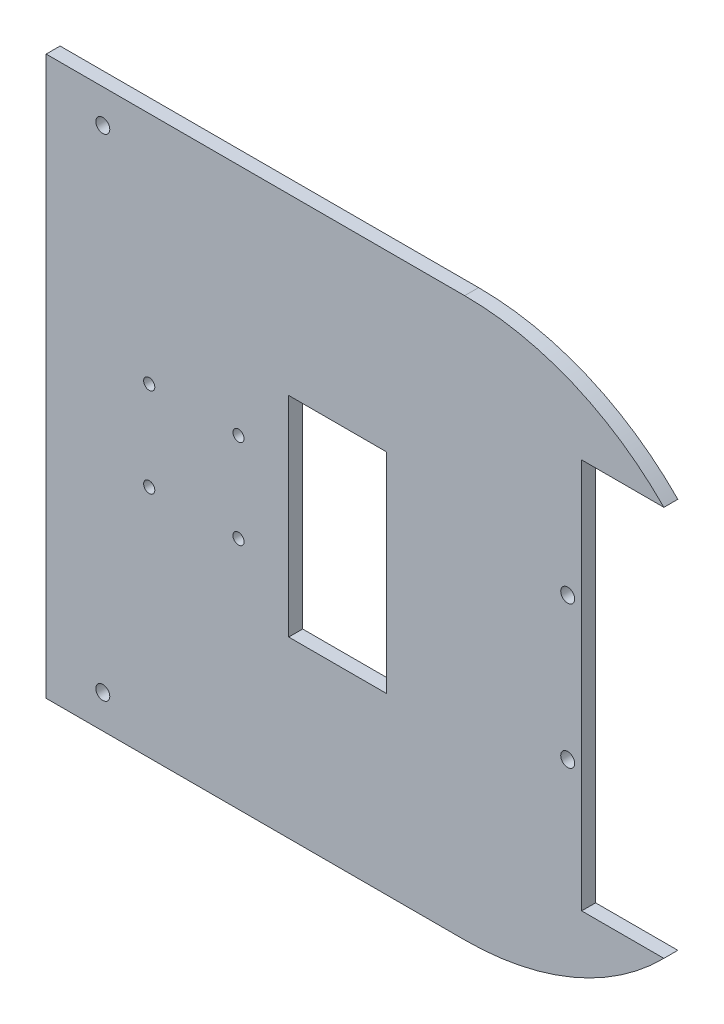
SolidWorks part; units mm, degrees
ref_plane "Front Plane" through (0, 0, 0) normal (0, 0, 1) x (1, 0, 0)
ref_plane "Top Plane" through (0, 0, 0) normal (0, 1, 0) x (1, 0, 0)
ref_plane "Right Plane" through (0, 0, 0) normal (1, 0, 0) x (0, 0, -1)
sketch "Sketch1" plane through (0, 0, 0) normal (0, 0, 1) x (1, 0, 0)
  line L0 (106.477, 150.6351) -> (77, 150.6351)
  line L1 (-264.9373, -19.3649) -> (35.0627, -19.3649)
  line L3 (-264.9373, 180.6351) -> (35.0627, 180.6351)
  line L5 (77, 150.6351) -> (77, 10.6351)
  line L6 (77, 10.6351) -> (106.477, 10.6351)
  line L8 (-306.8745, 10.6351) -> (-336.3515, 10.6351)
  line L9 (-306.8745, 150.6351) -> (-306.8745, 10.6351)
  line L10 (-336.3515, 150.6351) -> (-306.8745, 150.6351)
  arc A0 (35.0627, 180.6351) -> (35.0627, -19.3649) centre (35.0627, 80.6351) cw
  arc A1 (-264.9373, 180.6351) -> (-264.9373, -19.3649) centre (-264.9373, 80.6351) ccw
  point P0 (0, 0)
  point P2 (-364.9373, 80.6351)
  point P7 (135.0627, 80.6351)
  dimension "D2" = 100
  dimension "D3" = 180.6351
  dimension "D4" = 100
  dimension "D5" = 157.3021
  dimension "D6" = 373.7395
  dimension "D7" = 100
  dimension "D8" = 100
  dimension "D16" = 71.4143
  dimension "D15" = 30
  dimension "D1" = 200
  dimension "D9" = 30
  dimension "D10" = 30
  dimension "D11" = 77
  dimension "D12" = 270
  dimension "D13" = 383.8745
  dimension "D14" = 30
extrude "Boss-Extrude1" add sketch "Sketch1" against normal blind 5
sketch "Sketch2" plane through (0, 0, -5) normal (0, 0, -1) x (-1, 0, 0)
  line L5 (264.9373, -19.3649) -> (-35.0627, -19.3649) construction
  line L7 (114.9373, 180.6351) -> (114.9373, -19.3649) construction
  line L8 (264.9373, 180.6351) -> (-35.0627, 180.6351) construction
  line L15 (306.8745, 150.6351) -> (306.8745, 10.6351) construction
  line L16 (201.8745, 118.1351) -> (236.8745, 118.1351)
  line L17 (201.8745, 118.1351) -> (201.8745, 43.1351)
  line L18 (201.8745, 43.1351) -> (236.8745, 43.1351)
  line L19 (236.8745, 118.1351) -> (236.8745, 43.1351)
  line L20 (264.9373, -19.3649) -> (-35.0627, -19.3649) construction
  line L21 (28, 118.1351) -> (-7, 118.1351)
  line L22 (28, 118.1351) -> (28, 43.1351)
  line L23 (28, 43.1351) -> (-7, 43.1351)
  line L24 (-7, 118.1351) -> (-7, 43.1351)
  line L26 (306.8745, 80.6351) -> (-77, 80.6351) construction
  line L27 (-77, 150.6351) -> (-77, 10.6351) construction
  circle A0 centre (301.8745, 106.1351) radius 2.5
  circle A1 centre (301.8745, 55.1351) radius 2.5
  circle A2 centre (-72, 55.1351) radius 2.5
  circle A3 centre (-72, 106.1351) radius 2.5
  dimension "D6" = 25.5
  dimension "D7" = 5
  dimension "D8" = 5
  dimension "D1" = 70
  dimension "D2" = 75
  dimension "D3" = 35
  dimension "D4" = 62.5
  dimension "D5" = 201.8745
extrude "Cut-Extrude1" cut sketch "Sketch2" against normal blind 10
sketch "Sketch4" plane through (0, 0, -5) normal (0, 0, -1) x (-1, 0, 0)
  line L0 (264.9373, -19.3649) -> (-35.0627, -19.3649) construction
  line L1 (-77, 150.6351) -> (-77, 10.6351) construction
  line L2 (264.9373, 180.6351) -> (-35.0627, 180.6351) construction
  line L5 (114.9373, 180.6351) -> (114.9373, -19.3649) construction
  circle A0 centre (46, 64.6951) radius 2
  circle A1 centre (46, 96.6951) radius 2
  circle A2 centre (78, 64.6951) radius 2
  circle A3 centre (78, 96.6951) radius 2
  circle A4 centre (151.8745, 64.6951) radius 2
  circle A5 centre (183.8745, 64.6951) radius 2
  circle A6 centre (183.8745, 96.6951) radius 2
  circle A7 centre (151.8745, 96.6951) radius 2
  dimension "D1" = 84.06
  dimension "D2" = 123
  dimension "D3" = 4
  dimension "D4" = 83.94
  dimension "D6" = 4
  dimension "D7" = 155
  dimension "D8" = 155
  dimension "D9" = 83.94
  dimension "D5" = 123
  dimension "D10" = 84.06
extrude "Cut-Extrude3" cut sketch "Sketch4" against normal blind 10
sketch "Sketch5" plane through (0, 0, -5) normal (0, 0, -1) x (-1, 0, 0)
  line L0 (306.8745, 150.6351) -> (306.8745, 10.6351) construction
  line L1 (-77, 80.6351) -> (306.8745, 80.6351) construction
  line L2 (264.9373, 180.6351) -> (-35.0627, 180.6351) construction
  line L3 (-77, 150.6351) -> (-77, 10.6351) construction
  circle A2 centre (94.6373, 168.6351) radius 2.5
  circle A3 centre (135.2373, 168.6351) radius 2.5
  circle A4 centre (-72, 106.1351) radius 2.5 construction
  circle A7 centre (94.6373, -7.3649) radius 2.5
  circle A8 centre (135.2373, -7.3649) radius 2.5
  dimension "D1" = 40.6
  dimension "D2" = 12
  dimension "D3" = 12
  dimension "D4" = 171.6373
  dimension "D5" = 171.6373
extrude "Cut-Extrude4" cut sketch "Sketch5" against normal blind 10
sketch "Sketch6" plane through (0, 0, -5) normal (0, 0, -1) x (-1, 0, 0)
  line L0 (114.9373, 180.6351) -> (114.9373, -19.3649) construction
  line L1 (264.9373, 180.6351) -> (-35.0627, 180.6351) construction
  line L2 (264.9373, -19.3649) -> (-35.0627, -19.3649) construction
  line L3 (114.9373, 180.6351) -> (114.9373, -19.3649)
  line L4 (114.9373, -19.3649) -> (357.6914, -19.3649)
  line L5 (357.6914, -19.3649) -> (357.6914, 180.6351)
  line L6 (357.6914, 180.6351) -> (114.9373, 180.6351)
extrude "Cut-Extrude5" cut sketch "Sketch6" against normal blind 10
